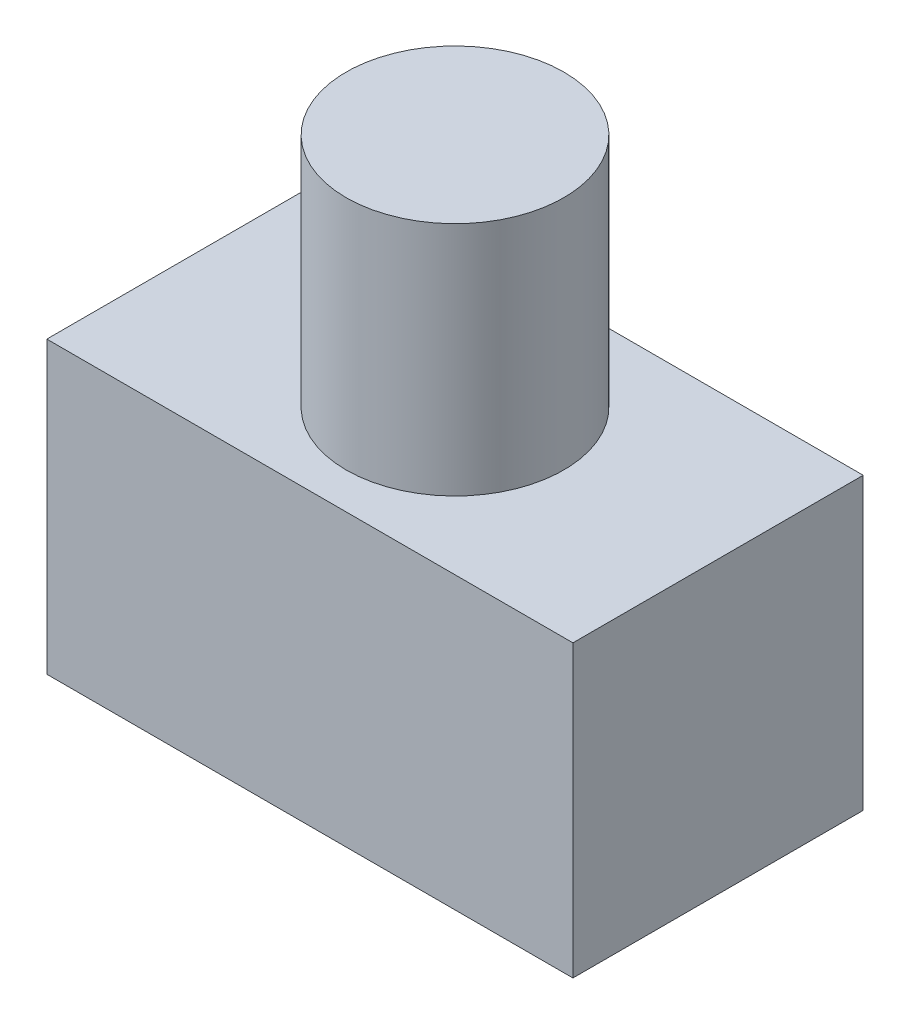
SolidWorks part; units mm, degrees
ref_plane "Front Plane" through (0, 0, 0) normal (0, 0, 1) x (1, 0, 0)
ref_plane "Top Plane" through (0, 0, 0) normal (0, 1, 0) x (1, 0, 0)
ref_plane "Right Plane" through (0, 0, 0) normal (1, 0, 0) x (0, 0, -1)
sketch "Sketch1" plane through (0, 0, 0) normal (0, 1, 0) x (1, 0, 0)
  line L1 (-14.5, 8) -> (14.5, 8)
  line L2 (-14.5, 8) -> (-14.5, -8)
  line L3 (-14.5, -8) -> (14.5, -8)
  line L4 (14.5, 8) -> (14.5, -8)
  line L5 (-14.5, 8) -> (14.5, -8) construction
  line L6 (-14.5, -8) -> (14.5, 8) construction
  point P0 (0, 0)
  dimension "D1" = 16
  dimension "D2" = 29
extrude "Boss-Extrude1" add sketch "Sketch1" along normal blind 16
sketch "Sketch2" plane through (0, 16, 0) normal (0, 1, 0) x (1, 0, 0)
  circle A0 centre (0, 0) radius 6
  dimension "D1" = 12
extrude "Boss-Extrude2" add sketch "Sketch2" along normal blind 13
